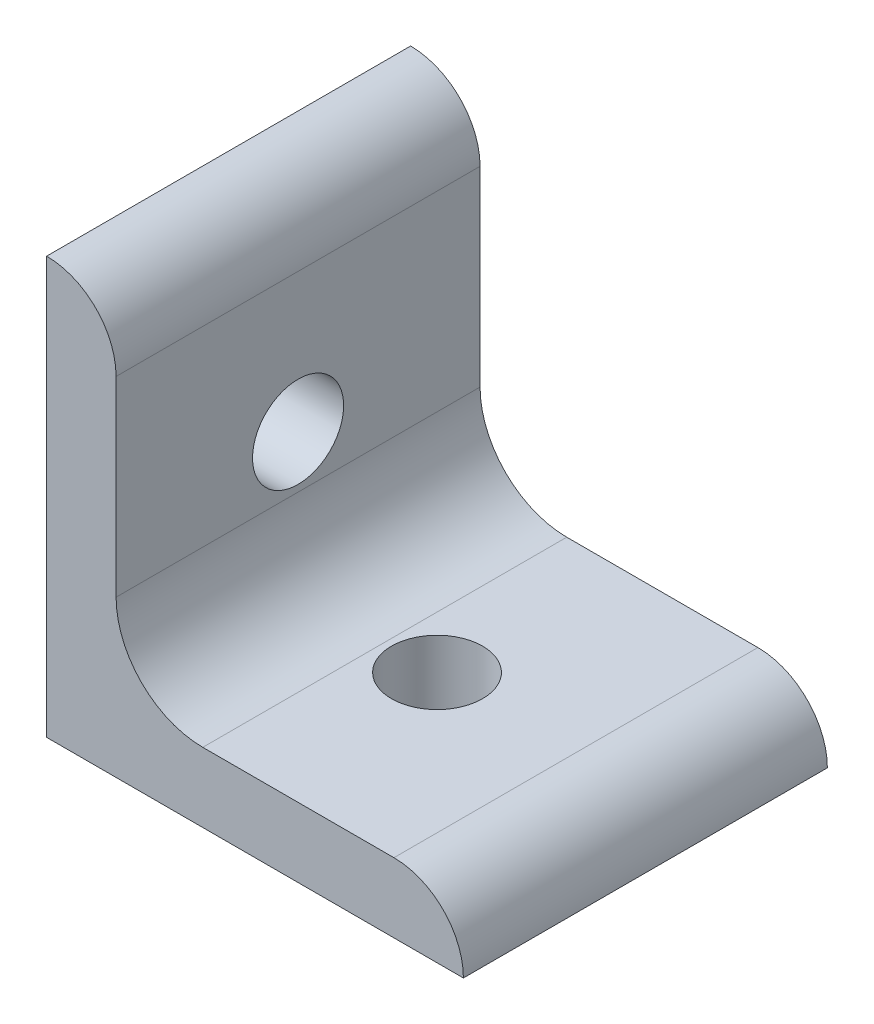
SolidWorks part; units mm, degrees
ref_plane "Front Plane" through (0, 0, 0) normal (0, 0, 1) x (1, 0, 0)
ref_plane "Top Plane" through (0, 0, 0) normal (0, 1, 0) x (1, 0, 0)
ref_plane "Right Plane" through (0, 0, 0) normal (1, 0, 0) x (0, 0, -1)
sketch "Sketch1" plane through (0, 0, 0) normal (0, 0, 1) x (1, 0, 0)
  line L0 (0, 0) -> (0, 38.1)
  line L1 (6.35, 31.75) -> (6.35, 38.1) construction
  line L2 (6.35, 31.75) -> (6.35, 14.2748)
  line L3 (14.2748, 6.35) -> (31.75, 6.35)
  line L4 (6.35, 38.1) -> (0, 38.1) construction
  line L5 (38.1, 0) -> (0, 0)
  line L6 (31.75, 6.35) -> (38.1, 6.35) construction
  line L7 (38.1, 6.35) -> (38.1, 0) construction
  arc A0 (6.35, 31.75) -> (0, 38.1) centre (0, 31.75) ccw
  arc A1 (38.1, 0) -> (31.75, 6.35) centre (31.75, 0) ccw
  arc A2 (6.35, 14.2748) -> (14.2748, 6.35) centre (14.2748, 14.2748) ccw
  point P10 (6.35, 34.925)
  dimension "E" = 7.9248
  dimension "D" = 6.35
  dimension "C" = 38.1
  dimension "B" = 38.1
extrude "Boss-Extrude1" add sketch "Sketch1" along normal mid plane 33.274
sketch "Sketch2" plane through (0, 0, 0) normal (0, 1, 0) x (1, 0, 0)
  line L0 (0, 0) -> (19.05, 0) construction
  circle A0 centre (19.05, 0) radius 4.1656
extrude "Cut-Extrude1" cut sketch "Sketch2" along normal through all
sketch "Sketch3" plane through (0, 0, 0) normal (1, 0, 0) x (0, 0, -1)
  line L0 (0, 0) -> (0, 19.05) construction
  circle A0 centre (0, 19.05) radius 4.1656
  dimension "D1" = 19.05
extrude "Cut-Extrude2" cut sketch "Sketch3" along normal through all
equation "\"E@Sketch3\" = \"E@Sketch2\""
equation "\"D1@Sketch3\" = \"D1@Sketch2\""
